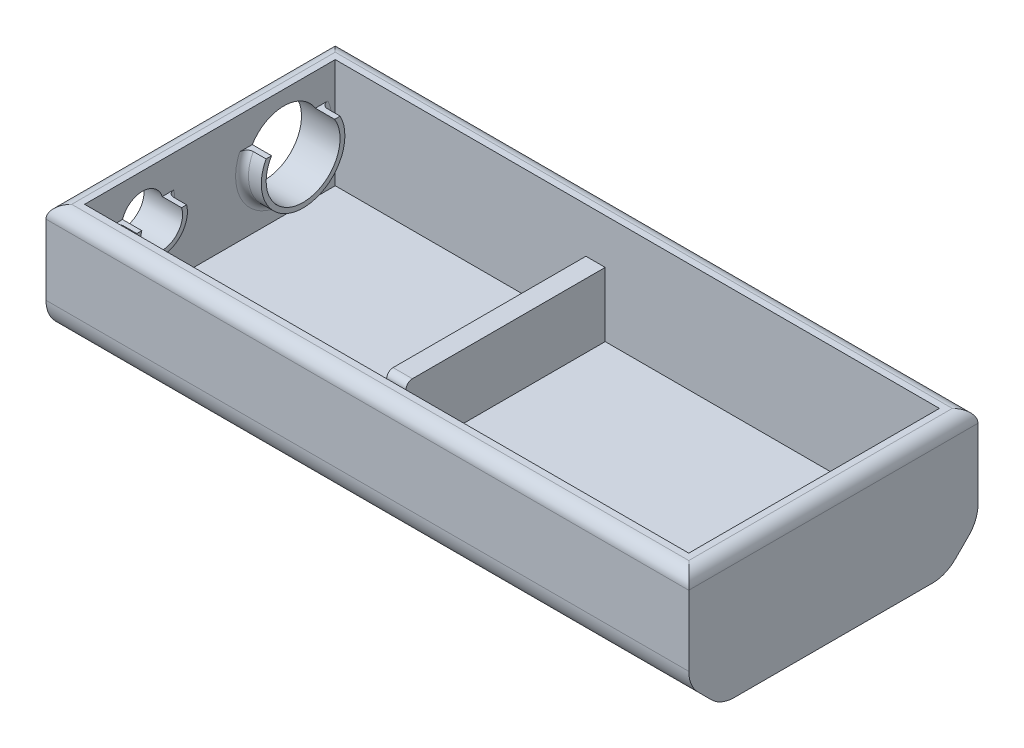
SolidWorks part; units mm, degrees
ref_plane "Front Plane" through (0, 0, 0) normal (0, 0, 1) x (1, 0, 0)
ref_plane "Top Plane" through (0, 0, 0) normal (0, 1, 0) x (1, 0, 0)
ref_plane "Right Plane" through (0, 0, 0) normal (1, 0, 0) x (0, 0, -1)
sketch "Sketch1" plane through (0, 0, 0) normal (0, 1, 0) x (1, 0, 0)
  line L1 (-50, 22.5) -> (50, 22.5)
  line L2 (-50, 22.5) -> (-50, -22.5)
  line L3 (-50, -22.5) -> (50, -22.5)
  line L4 (50, 22.5) -> (50, -22.5)
  line L5 (0, -22.5) -> (0, 22.5) construction
  line L6 (-50, 0) -> (50, 0) construction
  point P0 (0, 0)
  dimension "D1" = 100
  dimension "D2" = 45
extrude "Boss-Extrude1" add sketch "Sketch1" along normal blind 20
shell "Shell1" thickness 3
chamfer "Chamfer1" distance 5 angle 45 2 edges at (0, 0, -22.5) (0, 0, 22.5)
fillet "Fillet1" radius 5 4 edges at (0, 5, -22.5) (0, 0, -17.5) (0, 0, 17.5) (0, 5, 22.5)
sketch "Sketch2" plane through (-50, 0, 0) normal (-1, 0, 0) x (0, 0, 1)
  line L0 (-22.5, 20) -> (-22.5, 7.0711) construction
  line L1 (22.5, 20) -> (22.5, 7.0711) construction
  line L2 (-22.5, 20) -> (22.5, 20) construction
  circle A0 centre (-11.5, 12) radius 5.75
  circle A1 centre (10.5, 14) radius 3.25
  dimension "D1" = 11.5
  dimension "D3" = 6.5
  dimension "D2" = 11
  dimension "D4" = 12
  dimension "D5" = 8
  dimension "D6" = 6
extrude "Cut-Extrude1" cut sketch "Sketch2" against normal blind 20
sketch "Sketch3" plane through (-50, 0, 0) normal (-1, 0, 0) x (0, 0, 1)
  line L0 (-15.4289, 0) -> (15.4289, 0) construction
  circle A0 centre (13, 5) radius 1.5
  dimension "D1" = 3
  dimension "D2" = 5
extrude "Cut-Extrude2" cut sketch "Sketch3" against normal blind 10
sketch "Sketch4" plane through (-47, 0, 0) normal (1, 0, 0) x (0, 0, -1)
  line L0 (5.7337, 15) -> (6.5946, 15)
  line L1 (19.5, 20) -> (-19.5, 20) construction
  line L2 (16.4054, 15) -> (17.2663, 15)
  line L3 (-14.373, 15) -> (-13.5923, 15)
  line L4 (-7.4077, 15) -> (-6.627, 15)
  arc A0 (5.7337, 15) -> (17.2663, 15) centre (11.5, 12) ccw
  arc A1 (-14.373, 15) -> (-6.627, 15) centre (-10.5, 14) ccw
  arc A2 (6.5946, 15) -> (16.4054, 15) centre (11.5, 12) ccw
  arc A4 (-13.5923, 15) -> (-7.4077, 15) centre (-10.5, 14) ccw
  dimension "D1" = 13
  dimension "D2" = 5
  dimension "D3" = 8
  dimension "D4" = 5
extrude "Boss-Extrude2" add sketch "Sketch4" along normal blind 3
fillet "Fillet2" radius 1 2 edges at (-47, 10, 10.5) (-47, 5.5, -11.5)
sketch "Sketch5" plane through (0, 3, 0) normal (0, 1, 0) x (1, 0, 0)
  line L0 (47, 19.5) -> (-47, 19.5) construction
  line L1 (-8, -19.5) -> (-5, -19.5)
  line L2 (-8, -19.5) -> (-8, 19.5)
  line L3 (-8, 19.5) -> (-5, 19.5)
  line L4 (-5, -19.5) -> (-5, 19.5)
  line L5 (-6.5, 19.5) -> (-6.5, -19.5) construction
  line L6 (-8, 0) -> (-5, 0) construction
  line L7 (47, -19.5) -> (47, 19.5) construction
  point P0 (-6.5, 0)
  dimension "D1" = 52
  dimension "D2" = 3
extrude "Boss-Extrude3" add sketch "Sketch5" along normal blind 10
sketch "Sketch6" plane through (0, 13, 0) normal (0, 1, 0) x (1, 0, 0)
  line L0 (-8, 19.5) -> (-8, -19.5) construction
  line L1 (-8, -14.5) -> (-5, -14.5)
  line L2 (-8, -14.5) -> (-8, -11.5)
  line L3 (-8, -11.5) -> (-5, -11.5)
  line L4 (-5, -14.5) -> (-5, -11.5)
  line L5 (-5, -19.5) -> (-5, 19.5) construction
  line L6 (-8, -19.5) -> (-5, -19.5) construction
  dimension "D1" = 3
  dimension "D2" = 5
extrude "Cut-Extrude3" cut sketch "Sketch6" against normal blind 5
fillet "Fillet3" radius 1 2 edges at (-6.5, 13, 11.5) (-6.5, 13, 14.5)
fillet "Fillet4" radius 2 4 edges at (50, 20, 0) (0, 20, -22.5) (-50, 20, 0) (0, 20, 22.5)
fillet "Fillet6" radius 0.5 1 edges at (-50, 5, 14.5)
